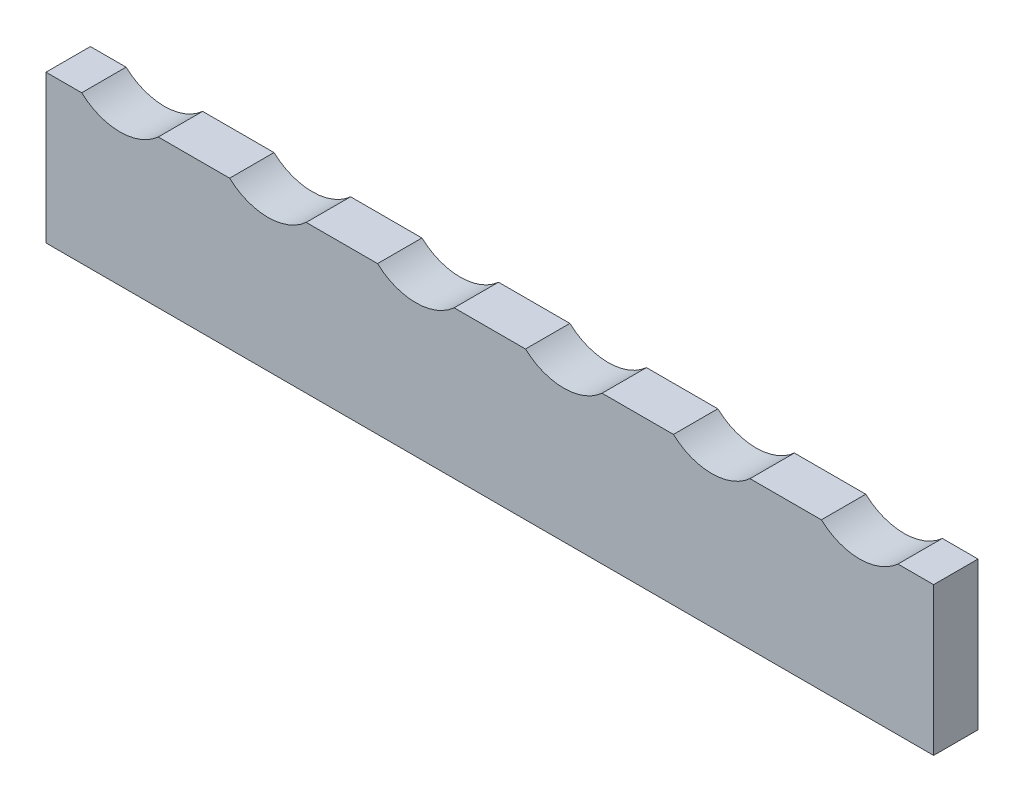
SolidWorks part; units mm, degrees
ref_plane "Front" through (0, 0, 0) normal (0, 0, 1) x (1, 0, 0)
ref_plane "Top" through (0, 0, 0) normal (0, 1, 0) x (1, 0, 0)
ref_plane "Right" through (0, 0, 0) normal (1, 0, 0) x (0, 0, -1)
sketch "Esquisse1" plane through (0, 0, 0) normal (0, 0, 1) x (1, 0, 0)
  line L0 (0, 0) -> (600, 0)
  line L1 (600, 0) -> (600, 100)
  line L2 (600, 100) -> (0, 100)
  line L3 (0, 100) -> (0, 0)
  dimension "D1" = 100
  dimension "D2" = 600
extrude "Boss.-Extru.1" add sketch "Esquisse1" along normal blind 30
sketch "Esquisse2" plane through (0, 0, 30) normal (0, 0, 1) x (1, 0, 0)
  line L0 (0, 100) -> (0, 0) construction
  line L1 (600, 100) -> (0, 100) construction
  line L2 (150, 128.5) -> (50, 128.5) construction
  circle A0 centre (50, 128.5) radius 38.5
  circle A1 centre (150, 128.5) radius 38.5
  circle A2 centre (250, 128.5) radius 38.5
  circle A3 centre (350, 128.5) radius 38.5
  circle A4 centre (450, 128.5) radius 38.5
  circle A5 centre (550, 128.5) radius 38.5
  dimension "D2" = 77
  dimension "D1" = 50
  dimension "D3" = 28.5
  dimension "D5" = 100
  dimension "D4" = 6
extrude "Enlèv. mat.-Extru.1" cut sketch "Esquisse2" against normal through all both and the other way through all
